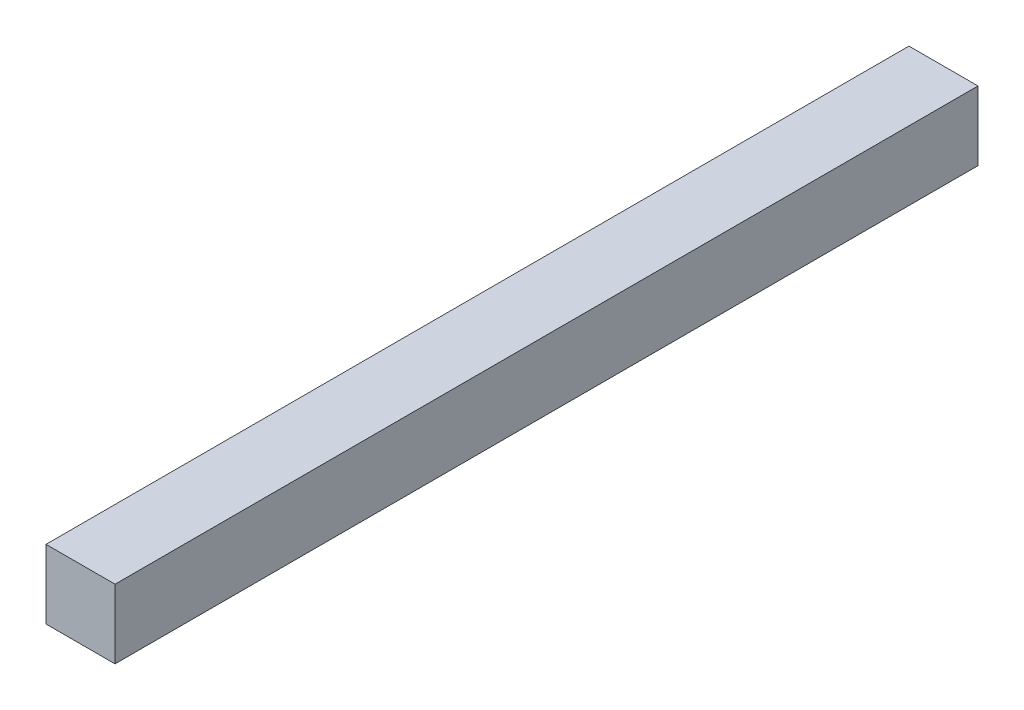
SolidWorks part; units mm, degrees
ref_plane "Front Plane" through (0, 0, 0) normal (0, 0, 1) x (1, 0, 0)
ref_plane "Top Plane" through (0, 0, 0) normal (0, 1, 0) x (1, 0, 0)
ref_plane "Right Plane" through (0, 0, 0) normal (1, 0, 0) x (0, 0, -1)
sketch "Sketch1" plane through (0, 0, 0) normal (0, 0, 1) x (1, 0, 0)
  line L1 (-8, -8) -> (8, -8)
  line L2 (-8, -8) -> (-8, 8)
  line L3 (-8, 8) -> (8, 8)
  line L4 (8, -8) -> (8, 8)
  line L5 (-8, -8) -> (8, 8) construction
  line L6 (-8, 8) -> (8, -8) construction
  point P0 (0, 0)
  dimension "D1" = 16
  dimension "D2" = 16
extrude "Boss-Extrude1" add sketch "Sketch1" along normal blind 200
